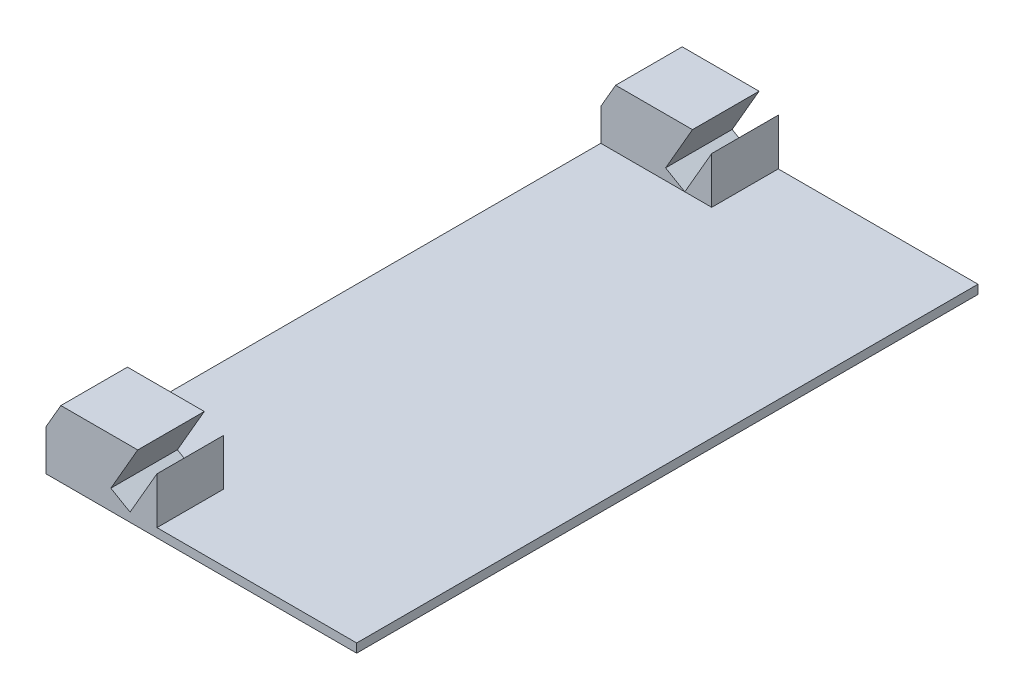
SolidWorks part; units mm, degrees
ref_plane "Ebene vorne" through (0, 0, 0) normal (0, 0, 1) x (1, 0, 0)
ref_plane "Ebene oben" through (0, 0, 0) normal (0, 1, 0) x (1, 0, 0)
ref_plane "Ebene rechts" through (0, 0, 0) normal (1, 0, 0) x (0, 0, -1)
sketch "Skizze1" plane through (0, 0, 0) normal (0, 1, 0) x (1, 0, 0)
  line L1 (-35, -70) -> (35, -70)
  line L2 (-35, -70) -> (-35, 70)
  line L3 (-35, 70) -> (35, 70)
  line L4 (35, -70) -> (35, 70)
  line L5 (-35, -70) -> (35, 70) construction
  line L6 (-35, 70) -> (35, -70) construction
  point P0 (0, 0)
  dimension "D1" = 140
  dimension "D2" = 70
extrude "Aufsatz-Linear austragen1" add sketch "Skizze1" along normal blind 2
sketch "Skizze2" plane through (0, 2, 0) normal (0, 1, 0) x (1, 0, 0)
  line L0 (35, 70) -> (-35, 70) construction
  line L1 (-35, 70) -> (-10, 70)
  line L2 (-35, 70) -> (-35, 55)
  line L3 (-35, 55) -> (-10, 55)
  line L4 (-10, 70) -> (-10, 55)
  line L5 (-35, 70) -> (-10, 55) construction
  line L6 (-35, 55) -> (-10, 70) construction
  line L7 (-35, -70) -> (-10, -70)
  line L8 (-35, -70) -> (-35, -55)
  line L9 (-35, -55) -> (-10, -55)
  line L10 (-10, -70) -> (-10, -55)
  line L11 (-35, -70) -> (-10, -55) construction
  line L12 (-35, -55) -> (-10, -70) construction
  line L13 (-35, -70) -> (35, -70) construction
  point P4 (-22.5, 62.5)
  point P10 (-22.5, -62.5)
  dimension "D1" = 25
  dimension "D2" = 25
  dimension "D3" = 15
  dimension "D4" = 15
extrude "Aufsatz-Linear austragen2" add sketch "Skizze2" along normal blind 13
sketch "Skizze3" plane through (0, 0, 70) normal (0, 0, 1) x (1, 0, 0)
  line L0 (-35, 9.1987) -> (-31.6506, 15)
  line L1 (-10, 2) -> (-23.2304, 2) construction
  line L2 (-35, 15) -> (-35, 0) construction
  line L3 (-35, 15) -> (-10, 15) construction
  line L4 (-31.6506, 15) -> (-18.6603, 7.5)
  line L5 (-18.6603, 7.5) -> (-14.3301, 15)
  line L6 (-18.6603, 7.5) -> (-14.3301, 5)
  line L7 (-14.3301, 15) -> (-10, 12.5)
  line L8 (-14.3301, 5) -> (-10, 12.5)
  line L9 (-10, 15) -> (-10, 2) construction
  line L12 (-18.6603, 7.5) -> (-14.3301, 5)
  line L13 (-18.6603, 7.5) -> (-20.3923, 4.5)
  line L14 (-14.3301, 5) -> (-16.0622, 2)
  line L15 (-20.3923, 4.5) -> (-16.0622, 2)
  line M6 (-10, 2) -> (-10, 15)
  line M7 (-10, 15) -> (-35, 15)
  line M8 (-35, 15) -> (-35, 0)
  dimension "D1" = 30
  dimension "D2" = 15
  dimension "D3" = 90
  dimension "D4" = 180
  dimension "D5" = 0
  dimension "D6" = 0
  dimension "D7" = 5
extrude "Schnitt-Linear austragen1" cut sketch "Skizze3" against normal through all contours L0 M8 M7 | L7 M7 M6 | L6 L8 L7 L5 M7 | L13 L15 L14 L6
